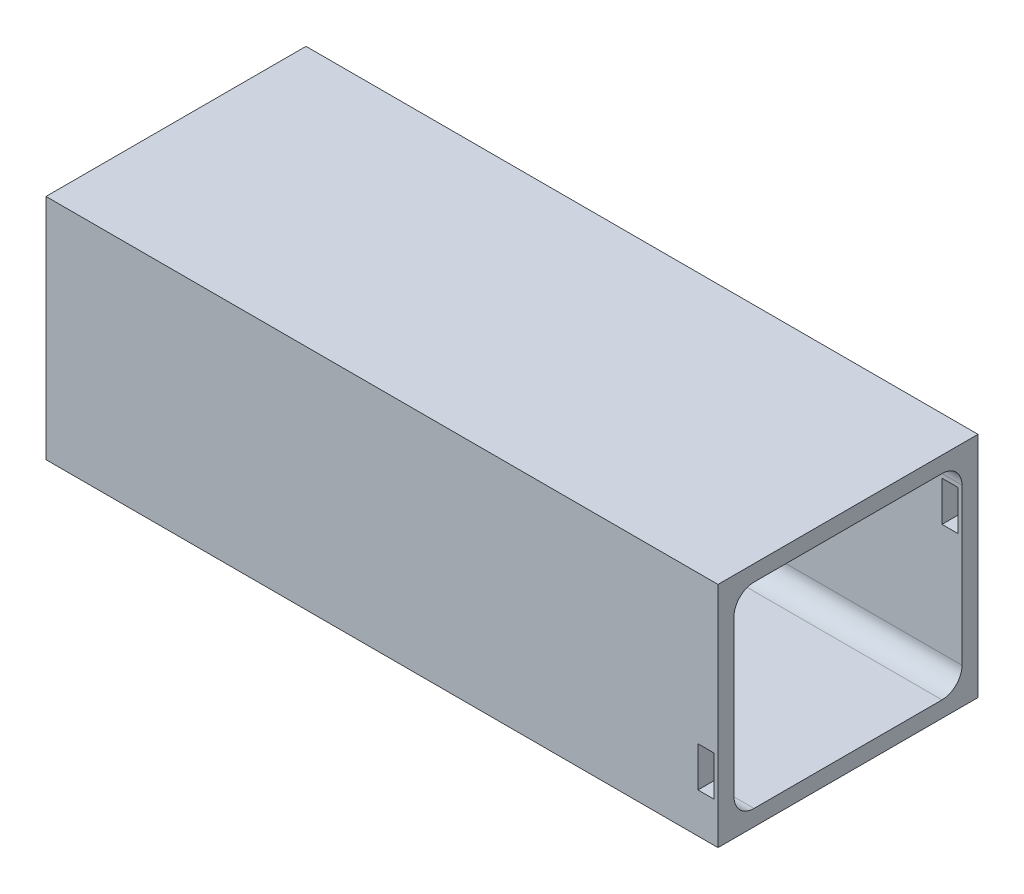
SolidWorks part; units mm, degrees
material "PET"
ref_plane "Спереди" through (0, 0, 0) normal (0, 0, 1) x (1, 0, 0)
ref_plane "Сверху" through (0, 0, 0) normal (0, 1, 0) x (1, 0, 0)
ref_plane "Справа" through (0, 0, 0) normal (1, 0, 0) x (0, 0, -1)
sketch "Эскиз1" plane through (0, 0, 0) normal (1, 0, 0) x (0, 0, -1)
  line L1 (23.5, -24.5) -> (-23.5, -24.5)
  line L2 (28.5, -19.5) -> (28.5, 19.5)
  line L3 (23.5, 24.5) -> (-23.5, 24.5)
  line L4 (-28.5, -19.5) -> (-28.5, 19.5)
  line L5 (28.5, -24.5) -> (-28.5, 24.5) construction
  line L6 (28.5, 24.5) -> (-28.5, -24.5) construction
  line L7 (32.5, -28.5) -> (-32.5, -28.5)
  line L8 (32.5, -28.5) -> (32.5, 28.5)
  line L9 (32.5, 28.5) -> (-32.5, 28.5)
  line L10 (-32.5, -28.5) -> (-32.5, 28.5)
  line L11 (32.5, -28.5) -> (-32.5, 28.5) construction
  line L12 (32.5, 28.5) -> (-32.5, -28.5) construction
  arc A0 (-23.5, -24.5) -> (-28.5, -19.5) centre (-23.5, -19.5) cw
  arc A1 (23.5, -24.5) -> (28.5, -19.5) centre (23.5, -19.5) ccw
  arc A2 (28.5, 19.5) -> (23.5, 24.5) centre (23.5, 19.5) ccw
  arc A3 (-23.5, 24.5) -> (-28.5, 19.5) centre (-23.5, 19.5) ccw
  point P0 (0, 0)
  point P5 (0, 0)
  dimension "D5" = 5
  dimension "D1" = 57
  dimension "D2" = 49
  dimension "D3" = 4
  dimension "D4" = 4
extrude "Бобышка-Вытянуть1" add sketch "Эскиз1" against normal blind 167
sketch "Эскиз2" plane through (0, 0, 32.5) normal (0, 0, 1) x (1, 0, 0)
  line L0 (0, 28.5) -> (0, -28.5) construction
  line L1 (-1, -18.5) -> (-5, -18.5)
  line L2 (-1, -18.5) -> (-1, -8.5)
  line L3 (-1, -8.5) -> (-5, -8.5)
  line L4 (-5, -18.5) -> (-5, -8.5)
  line L5 (-167, -28.5) -> (0, -28.5) construction
  dimension "D1" = 4
  dimension "D2" = 10
  dimension "D3" = 1
  dimension "D4" = 10
extrude "Вырез-Вытянуть1" cut sketch "Эскиз2" against normal blind 10
sketch "Эскиз3" plane through (-167, 0, 0) normal (-1, 0, 0) x (0, 0, 1)
  line L1 (32.5, -28.5) -> (-32.5, -28.5)
  line L2 (32.5, -28.5) -> (32.5, 28.5)
  line L3 (32.5, 28.5) -> (-32.5, 28.5)
  line L4 (-32.5, -28.5) -> (-32.5, 28.5)
  line L5 (32.5, -28.5) -> (-32.5, 28.5) construction
  line L6 (32.5, 28.5) -> (-32.5, -28.5) construction
  point P0 (0, 0)
extrude "Бобышка-Вытянуть2" add sketch "Эскиз3" along normal blind 1
sketch "Эскиз4" plane through (0, 0, -32.5) normal (0, 0, -1) x (-1, 0, 0)
  line L0 (168, 28.5) -> (0, 28.5) construction
  line L1 (1, 18.5) -> (5, 18.5)
  line L2 (1, 18.5) -> (1, 8.5)
  line L3 (1, 8.5) -> (5, 8.5)
  line L4 (5, 18.5) -> (5, 8.5)
  line L5 (0, -28.5) -> (0, 28.5) construction
  dimension "D1" = 10
  dimension "D2" = 1
  dimension "D3" = 10
  dimension "D4" = 4
extrude "Вырез-Вытянуть2" cut sketch "Эскиз4" against normal blind 10
